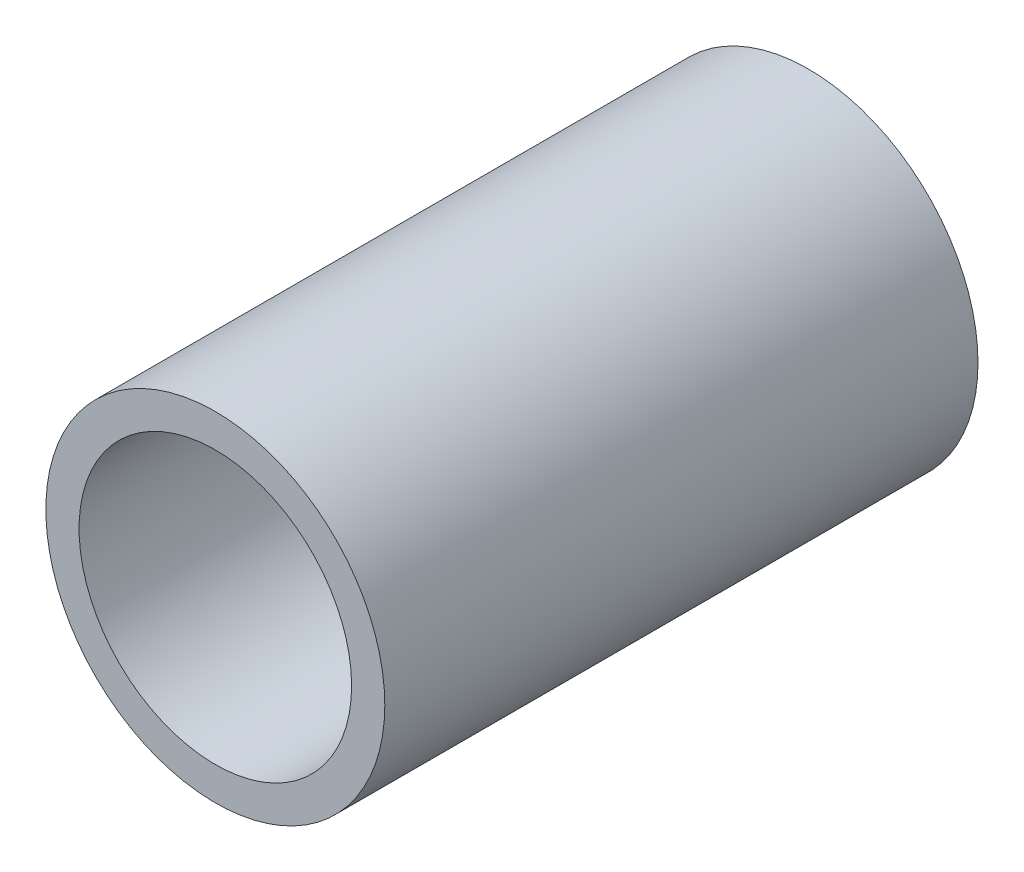
SolidWorks part; units mm, degrees
ref_plane "Front Plane" through (0, 0, 0) normal (0, 0, 1) x (1, 0, 0)
ref_plane "Top Plane" through (0, 0, 0) normal (0, 1, 0) x (1, 0, 0)
ref_plane "Right Plane" through (0, 0, 0) normal (1, 0, 0) x (0, 0, -1)
sketch "Sketch1" plane through (0, 0, 0) normal (0, 0, 1) x (1, 0, 0)
  circle A0 centre (0, 0) radius 20
  dimension "D1" = 40
extrude "Boss-Extrude1" add sketch "Sketch1" along normal blind 70
sketch "Sketch2" plane through (0, 0, 70) normal (0, 0, 1) x (1, 0, 0)
  circle A0 centre (0, 0) radius 16.0813
  circle A1 centre (0, 0) radius 20 construction
  dimension "D1" = 3.9187
extrude "Cut-Extrude1" cut sketch "Sketch2" against normal blind 60
